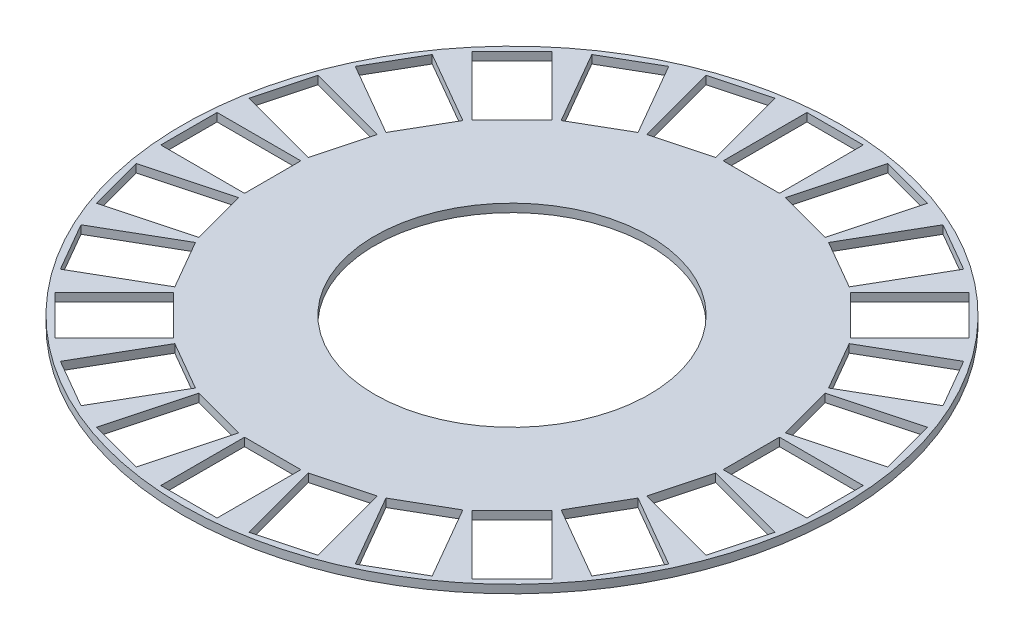
SolidWorks part; units mm, degrees
ref_plane "Front Plane" through (0, 0, 0) normal (0, 0, 1) x (1, 0, 0)
ref_plane "Top Plane" through (0, 0, 0) normal (0, 1, 0) x (1, 0, 0)
ref_plane "Right Plane" through (0, 0, 0) normal (1, 0, 0) x (0, 0, -1)
sketch "Sketch1" plane through (0, 0, 0) normal (0, 1, 0) x (1, 0, 0)
  line L0 (13.9624, -56.2789) -> (-5.914, -58.8957) construction
  line L1 (113.346, 43.1948) -> (14.2015, 56.2475) construction
  line L2 (-36.8008, 0) -> (-21.3612, 0) construction
  line L3 (0, 32.128) -> (0, 12.986) construction
  line L6 (-4.9791, 63.8158) -> (118.9515, 47.5) construction
  line L7 (-4.9791, 63.8158) -> (-5.2391, 63.85)
  line L8 (118.9515, 47.5) -> (9.893, 61.8578) construction
  line L9 (9.6329, -61.8921) -> (118.6849, -47.5351) construction
  line L10 (-4.9791, -63.8158) -> (-3.1376, -63.5733) construction
  line L11 (-4.9791, -63.8158) -> (-5.2391, -63.85) construction
  line L18 (-20.3346, 15.6631) -> (0, 12.986)
  line L22 (-20.3346, -15.6631) -> (0, -12.986)
  line L23 (-20.3346, 15.6631) -> (0, 12.986)
  line L24 (-12.2267, 45.922) -> (24.7284, 30.6147) construction
  line L25 (-12.2267, 45.922) -> (24.7284, 30.6147) construction
  line L26 (3.4364, 73.0514) -> (35.1705, 48.7009)
  line L27 (3.4364, 73.0514) -> (35.1705, 48.7009)
  line L28 (25.5874, 95.2024) -> (49.9379, 63.4683) construction
  line L29 (25.5874, 95.2024) -> (49.9379, 63.4683) construction
  line L30 (52.7168, 110.8655) -> (68.0241, 73.9104) construction
  line L31 (52.7168, 110.8655) -> (68.0241, 73.9104) construction
  line L32 (82.9757, 118.9734) -> (88.1967, 79.3156) construction
  line L33 (82.9757, 118.9734) -> (88.1967, 79.3156) construction
  line L34 (114.3019, 118.9734) -> (109.0809, 79.3156) construction
  line L35 (114.3019, 118.9734) -> (109.0809, 79.3156) construction
  line L36 (144.5608, 110.8655) -> (129.2535, 73.9104) construction
  line L37 (144.5608, 110.8655) -> (129.2535, 73.9104) construction
  line L38 (171.6902, 95.2024) -> (147.3397, 63.4683) construction
  line L39 (171.6902, 95.2024) -> (147.3397, 63.4683) construction
  line L40 (193.8412, 73.0514) -> (162.1071, 48.7009) construction
  line L41 (193.8412, 73.0514) -> (162.1071, 48.7009) construction
  line L42 (209.5043, 45.922) -> (172.5492, 30.6147) construction
  line L43 (209.5043, 45.922) -> (172.5492, 30.6147) construction
  line L44 (217.6122, 15.6631) -> (177.9544, 10.4421) construction
  line L45 (217.6122, 15.6631) -> (177.9544, 10.4421) construction
  line L46 (217.6122, -15.6631) -> (177.9544, -10.4421) construction
  line L47 (217.6122, -15.6631) -> (177.9544, -10.4421) construction
  line L48 (209.5043, -45.922) -> (172.5492, -30.6147) construction
  line L49 (209.5043, -45.922) -> (172.5492, -30.6147) construction
  line L50 (193.8412, -73.0514) -> (162.1071, -48.7009) construction
  line L51 (193.8412, -73.0514) -> (162.1071, -48.7009) construction
  line L52 (171.6902, -95.2024) -> (147.3397, -63.4683) construction
  line L53 (171.6902, -95.2024) -> (147.3397, -63.4683) construction
  line L54 (144.5608, -110.8655) -> (129.2535, -73.9104) construction
  line L55 (144.5608, -110.8655) -> (129.2535, -73.9104) construction
  line L56 (114.3019, -118.9734) -> (109.0809, -79.3156) construction
  line L57 (114.3019, -118.9734) -> (109.0809, -79.3156) construction
  line L58 (82.9757, -118.9734) -> (88.1967, -79.3156) construction
  line L59 (82.9757, -118.9734) -> (88.1967, -79.3156) construction
  line L60 (52.7168, -110.8655) -> (68.0241, -73.9104) construction
  line L61 (52.7168, -110.8655) -> (68.0241, -73.9104) construction
  line L62 (25.5874, -95.2024) -> (49.9379, -63.4683) construction
  line L63 (25.5874, -95.2024) -> (49.9379, -63.4683) construction
  line L64 (19.7081, -60.5656) -> (35.1705, -48.7009)
  line L65 (19.7081, -60.5656) -> (35.1705, -48.7009)
  line L66 (-12.2267, -45.922) -> (24.7284, -30.6147) construction
  line L67 (-12.2267, -45.922) -> (24.7284, -30.6147) construction
  line L68 (-20.3346, -15.6631) -> (0, -12.986)
  line L69 (0, 12.986) -> (19.3232, 10.4421) construction
  line L70 (0, 12.986) -> (19.3232, 10.4421) construction
  line L71 (0, 12.986) -> (0, 0) construction
  line L72 (0, -12.986) -> (0, -36.1975) construction
  line L73 (-21.3612, 0) -> (0, 0) construction
  line L74 (0, 0) -> (38.6388, 0) construction
  line L75 (0, 0) -> (0, -12.986) construction
  line L76 (0, -12.986) -> (19.3232, -10.4421) construction
  line L77 (0, -12.986) -> (19.3232, -10.4421) construction
  line L78 (-5.914, -58.8957) -> (38.73, -53.0182) construction
  line L79 (38.73, -53.0182) -> (113.1069, -43.2263) construction
  line L80 (13.9624, -56.2789) -> (113.1069, -43.2263) construction
  line L81 (-3.1376, -63.5733) -> (19.7081, -60.5656) construction
  line L82 (19.7081, -60.5656) -> (118.6849, -47.5351) construction
  line L83 (3.4364, -73.0514) -> (19.7081, -60.5656) construction
  line L84 (3.4364, -73.0514) -> (19.7081, -60.5656) construction
  arc A0 (14.2015, 56.2475) -> (13.9624, -56.2789) centre (470.8487, -0.9863) ccw construction
  arc A1 (113.346, 43.1948) -> (113.1069, -43.2263) centre (470.697, -1.0048) ccw construction
  arc A2 (118.9515, 47.5) -> (118.6849, -47.5351) centre (470.697, -1.0048) ccw construction
  arc A4 (-5.2391, -63.85) -> (-4.9791, 63.8158) centre (470.8487, -0.9863) cw construction
  arc A5 (9.893, 61.8578) -> (9.6329, -61.8921) centre (470.8487, -0.9863) ccw construction
  arc A8 (-20.3346, -15.6631) -> (-20.3346, 15.6631) centre (98.6388, 0) cw
  arc A9 (19.3232, 10.4421) -> (18.6779, 2.5) centre (98.6388, 0) ccw
  arc A10 (24.7284, 30.6147) -> (19.3232, 10.4421) centre (98.6388, 0) ccw
  arc A11 (-20.3346, 15.6631) -> (-12.2267, 45.922) centre (98.6388, 0) cw
  arc A12 (35.1705, 48.7009) -> (24.7284, 30.6147) centre (98.6388, 0) ccw
  arc A13 (-12.2267, 45.922) -> (3.4364, 73.0514) centre (98.6388, 0) cw
  arc A14 (49.9379, 63.4683) -> (35.1705, 48.7009) centre (98.6388, 0) ccw
  arc A15 (3.4364, 73.0514) -> (25.5874, 95.2024) centre (98.6388, 0) cw
  arc A16 (68.0241, 73.9104) -> (49.9379, 63.4683) centre (98.6388, 0) ccw
  arc A17 (25.5874, 95.2024) -> (52.7168, 110.8655) centre (98.6388, 0) cw
  arc A18 (88.1967, 79.3156) -> (68.0241, 73.9104) centre (98.6388, 0) ccw
  arc A19 (52.7168, 110.8655) -> (82.9757, 118.9734) centre (98.6388, 0) cw
  arc A20 (109.0809, 79.3156) -> (88.1967, 79.3156) centre (98.6388, 0) ccw
  arc A21 (82.9757, 118.9734) -> (114.3019, 118.9734) centre (98.6388, 0) cw
  arc A22 (129.2535, 73.9104) -> (109.0809, 79.3156) centre (98.6388, 0) ccw
  arc A23 (114.3019, 118.9734) -> (144.5608, 110.8655) centre (98.6388, 0) cw
  arc A24 (147.3397, 63.4683) -> (129.2535, 73.9104) centre (98.6388, 0) ccw
  arc A25 (144.5608, 110.8655) -> (171.6902, 95.2024) centre (98.6388, 0) cw
  arc A26 (162.1071, 48.7009) -> (147.3397, 63.4683) centre (98.6388, 0) ccw
  arc A27 (171.6902, 95.2024) -> (193.8412, 73.0514) centre (98.6388, 0) cw
  arc A28 (172.5492, 30.6147) -> (162.1071, 48.7009) centre (98.6388, 0) ccw
  arc A29 (193.8412, 73.0514) -> (209.5043, 45.922) centre (98.6388, 0) cw
  arc A30 (177.9544, 10.4421) -> (172.5492, 30.6147) centre (98.6388, 0) ccw
  arc A31 (209.5043, 45.922) -> (217.6122, 15.6631) centre (98.6388, 0) cw
  arc A32 (177.9544, -10.4421) -> (177.9544, 10.4421) centre (98.6388, 0) ccw
  arc A33 (217.6122, 15.6631) -> (217.6122, -15.6631) centre (98.6388, 0) cw
  arc A34 (172.5492, -30.6147) -> (177.9544, -10.4421) centre (98.6388, 0) ccw
  arc A35 (217.6122, -15.6631) -> (209.5043, -45.922) centre (98.6388, 0) cw
  arc A36 (162.1071, -48.7009) -> (172.5492, -30.6147) centre (98.6388, 0) ccw
  arc A37 (209.5043, -45.922) -> (193.8412, -73.0514) centre (98.6388, 0) cw
  arc A38 (147.3397, -63.4683) -> (162.1071, -48.7009) centre (98.6388, 0) ccw
  arc A39 (193.8412, -73.0514) -> (171.6902, -95.2024) centre (98.6388, 0) cw
  arc A40 (129.2535, -73.9104) -> (147.3397, -63.4683) centre (98.6388, 0) ccw
  arc A41 (171.6902, -95.2024) -> (144.5608, -110.8655) centre (98.6388, 0) cw
  arc A42 (109.0809, -79.3156) -> (129.2535, -73.9104) centre (98.6388, 0) ccw
  arc A43 (144.5608, -110.8655) -> (114.3019, -118.9734) centre (98.6388, 0) cw
  arc A44 (88.1967, -79.3156) -> (109.0809, -79.3156) centre (98.6388, 0) ccw
  arc A45 (114.3019, -118.9734) -> (82.9757, -118.9734) centre (98.6388, 0) cw
  arc A46 (68.0241, -73.9104) -> (88.1967, -79.3156) centre (98.6388, 0) ccw
  arc A47 (82.9757, -118.9734) -> (52.7168, -110.8655) centre (98.6388, 0) cw
  arc A48 (49.9379, -63.4683) -> (68.0241, -73.9104) centre (98.6388, 0) ccw
  arc A49 (52.7168, -110.8655) -> (25.5874, -95.2024) centre (98.6388, 0) cw
  arc A50 (35.1705, -48.7009) -> (49.9379, -63.4683) centre (98.6388, 0) ccw
  arc A51 (25.5874, -95.2024) -> (3.4364, -73.0514) centre (98.6388, 0) cw
  arc A52 (24.7284, -30.6147) -> (35.1705, -48.7009) centre (98.6388, 0) ccw
  arc A53 (3.4364, -73.0514) -> (-12.2267, -45.922) centre (98.6388, 0) cw
  arc A54 (19.3232, -10.4421) -> (24.7284, -30.6147) centre (98.6388, 0) ccw
  arc A55 (-12.2267, -45.922) -> (-20.3346, -15.6631) centre (98.6388, 0) cw
  arc A56 (18.6779, 2.5) -> (18.6388, 0) centre (98.6388, 0) ccw
  arc A57 (18.6779, -2.5) -> (19.3232, -10.4421) centre (98.6388, 0) ccw
  arc A58 (18.6388, 0) -> (18.6779, -2.5) centre (98.6388, 0) ccw
  circle A59 centre (98.6388, 0) radius 80
  circle A60 centre (98.6388, 0) radius 50
  point P21 (0, 0)
  point P123 (98.6388, 0)
  dimension "D1" = 47.5
  dimension "D2" = 63.85
  dimension "D4" = 100
  dimension "D8" = 125
  dimension "D10" = 80
  dimension "D11" = 120
  dimension "D13" = 100
  dimension "D3" = 7.5
  dimension "D5" = 100
  dimension "D7" = 40
  dimension "D9" = 24
  dimension "D12" = 7.5
  dimension "D6" = 5
extrude "Boss-Extrude1" add sketch "Sketch1" along normal mid plane 3
sketch "Sketch6" plane through (0, 1.5, 0) normal (0, 1, 0) x (1, 0, 0)
  line L0 (18.6388, 0) -> (0, 0) construction
  line L1 (-19, 10.25) -> (11.5, 10.25)
  line L2 (-19, 10.25) -> (-19, -10.25)
  line L3 (-19, -10.25) -> (11.5, -10.25)
  line L4 (11.5, 10.25) -> (11.5, -10.25)
  line L5 (-19, 10.25) -> (11.5, -10.25) construction
  line L6 (-19, -10.25) -> (11.5, 10.25) construction
  line L7 (-12.3387, 40.3479) -> (-17.6445, 20.5464)
  line L8 (-12.3387, 40.3479) -> (17.1221, 32.4539)
  line L9 (17.1221, 32.4539) -> (11.8163, 12.6524)
  line L10 (-17.6445, 20.5464) -> (11.8163, 12.6524)
  line L11 (1.8856, 67.6962) -> (-8.3644, 49.9426)
  line L12 (1.8856, 67.6962) -> (28.2994, 52.4462)
  line L13 (28.2994, 52.4462) -> (18.0494, 34.6926)
  line L14 (-8.3644, 49.9426) -> (18.0494, 34.6926)
  line L15 (22.7035, 90.431) -> (8.2078, 75.9353)
  line L16 (22.7035, 90.431) -> (44.2702, 68.8643)
  line L17 (44.2702, 68.8643) -> (29.7745, 54.3686)
  line L18 (8.2078, 75.9353) -> (29.7745, 54.3686)
  line L19 (48.6962, 107.0032) -> (30.9426, 96.7532)
  line L20 (48.6962, 107.0032) -> (63.9462, 80.5894)
  line L21 (63.9462, 80.5894) -> (46.1926, 70.3394)
  line L22 (30.9426, 96.7532) -> (46.1926, 70.3394)
  line L23 (78.0924, 116.2832) -> (58.2909, 110.9775)
  line L24 (78.0924, 116.2832) -> (85.9864, 86.8225)
  line L25 (85.9864, 86.8225) -> (66.1849, 81.5167)
  line L26 (58.2909, 110.9775) -> (66.1849, 81.5167)
  line L27 (108.8888, 117.6388) -> (88.3888, 117.6388)
  line L28 (108.8888, 117.6388) -> (108.8888, 87.1388)
  line L29 (108.8888, 87.1388) -> (88.3888, 87.1388)
  line L30 (88.3888, 117.6388) -> (88.3888, 87.1388)
  line L31 (138.9867, 110.9775) -> (119.1852, 116.2832)
  line L32 (138.9867, 110.9775) -> (131.0927, 81.5167)
  line L33 (131.0927, 81.5167) -> (111.2912, 86.8225)
  line L34 (119.1852, 116.2832) -> (111.2912, 86.8225)
  line L35 (166.335, 96.7532) -> (148.5814, 107.0032)
  line L36 (166.335, 96.7532) -> (151.085, 70.3394)
  line L37 (151.085, 70.3394) -> (133.3314, 80.5894)
  line L38 (148.5814, 107.0032) -> (133.3314, 80.5894)
  line L39 (189.0698, 75.9353) -> (174.5741, 90.431)
  line L40 (189.0698, 75.9353) -> (167.5031, 54.3686)
  line L41 (167.5031, 54.3686) -> (153.0074, 68.8643)
  line L42 (174.5741, 90.431) -> (153.0074, 68.8643)
  line L43 (205.642, 49.9426) -> (195.392, 67.6962)
  line L44 (205.642, 49.9426) -> (179.2282, 34.6926)
  line L45 (179.2282, 34.6926) -> (168.9782, 52.4462)
  line L46 (195.392, 67.6962) -> (168.9782, 52.4462)
  line L47 (214.922, 20.5464) -> (209.6163, 40.3479)
  line L48 (214.922, 20.5464) -> (185.4613, 12.6524)
  line L49 (185.4613, 12.6524) -> (180.1555, 32.4539)
  line L50 (209.6163, 40.3479) -> (180.1555, 32.4539)
  line L51 (216.2776, -10.25) -> (216.2776, 10.25)
  line L52 (216.2776, -10.25) -> (185.7776, -10.25)
  line L53 (185.7776, -10.25) -> (185.7776, 10.25)
  line L54 (216.2776, 10.25) -> (185.7776, 10.25)
  line L55 (209.6163, -40.3479) -> (214.922, -20.5464)
  line L56 (209.6163, -40.3479) -> (180.1555, -32.4539)
  line L57 (180.1555, -32.4539) -> (185.4613, -12.6524)
  line L58 (214.922, -20.5464) -> (185.4613, -12.6524)
  line L59 (195.392, -67.6962) -> (205.642, -49.9426)
  line L60 (195.392, -67.6962) -> (168.9782, -52.4462)
  line L61 (168.9782, -52.4462) -> (179.2282, -34.6926)
  line L62 (205.642, -49.9426) -> (179.2282, -34.6926)
  line L63 (174.5741, -90.431) -> (189.0698, -75.9353)
  line L64 (174.5741, -90.431) -> (153.0074, -68.8643)
  line L65 (153.0074, -68.8643) -> (167.5031, -54.3686)
  line L66 (189.0698, -75.9353) -> (167.5031, -54.3686)
  line L67 (148.5814, -107.0032) -> (166.335, -96.7532)
  line L68 (148.5814, -107.0032) -> (133.3314, -80.5894)
  line L69 (133.3314, -80.5894) -> (151.085, -70.3394)
  line L70 (166.335, -96.7532) -> (151.085, -70.3394)
  line L71 (119.1852, -116.2832) -> (138.9867, -110.9775)
  line L72 (119.1852, -116.2832) -> (111.2912, -86.8225)
  line L73 (111.2912, -86.8225) -> (131.0927, -81.5167)
  line L74 (138.9867, -110.9775) -> (131.0927, -81.5167)
  line L75 (88.3888, -117.6388) -> (108.8888, -117.6388)
  line L76 (88.3888, -117.6388) -> (88.3888, -87.1388)
  line L77 (88.3888, -87.1388) -> (108.8888, -87.1388)
  line L78 (108.8888, -117.6388) -> (108.8888, -87.1388)
  line L79 (58.2909, -110.9775) -> (78.0924, -116.2832)
  line L80 (58.2909, -110.9775) -> (66.1849, -81.5167)
  line L81 (66.1849, -81.5167) -> (85.9864, -86.8225)
  line L82 (78.0924, -116.2832) -> (85.9864, -86.8225)
  line L83 (30.9426, -96.7532) -> (48.6962, -107.0032)
  line L84 (30.9426, -96.7532) -> (46.1926, -70.3394)
  line L85 (46.1926, -70.3394) -> (63.9462, -80.5894)
  line L86 (48.6962, -107.0032) -> (63.9462, -80.5894)
  line L87 (8.2078, -75.9353) -> (22.7035, -90.431)
  line L88 (8.2078, -75.9353) -> (29.7745, -54.3686)
  line L89 (29.7745, -54.3686) -> (44.2702, -68.8643)
  line L90 (22.7035, -90.431) -> (44.2702, -68.8643)
  line L91 (-8.3644, -49.9426) -> (1.8856, -67.6962)
  line L92 (-8.3644, -49.9426) -> (18.0494, -34.6926)
  line L93 (18.0494, -34.6926) -> (28.2994, -52.4462)
  line L94 (1.8856, -67.6962) -> (28.2994, -52.4462)
  line L95 (-17.6445, -20.5464) -> (-12.3387, -40.3479)
  line L96 (-17.6445, -20.5464) -> (11.8163, -12.6524)
  line L97 (11.8163, -12.6524) -> (17.1221, -32.4539)
  line L98 (-12.3387, -40.3479) -> (17.1221, -32.4539)
  circle A0 centre (98.6388, 0) radius 80 construction
  point P0 (-3.75, 0)
  point P104 (98.6388, 0)
  dimension "D1" = 20.5
  dimension "D2" = 30.5
  dimension "D3" = 3.75
  dimension "D4" = 24
extrude "Cut-Extrude1" cut sketch "Sketch6" against normal blind 10.5
